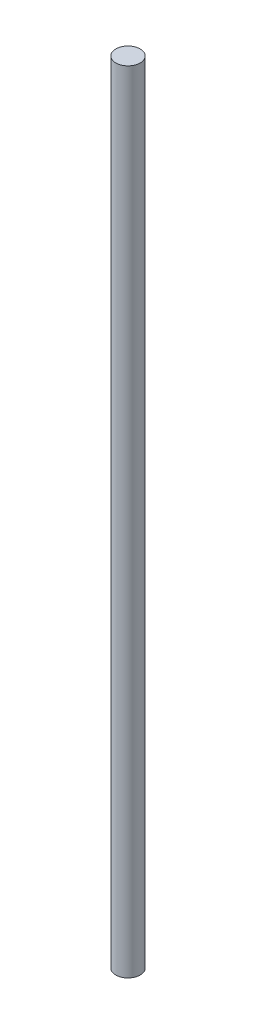
SolidWorks part; units mm, degrees
material "PVC 0.007 Plasticized"
ref_plane "Front Plane" through (0, 0, 0) normal (0, 0, 1) x (1, 0, 0)
ref_plane "Top Plane" through (0, 0, 0) normal (0, 1, 0) x (1, 0, 0)
ref_plane "Right Plane" through (0, 0, 0) normal (1, 0, 0) x (0, 0, -1)
sketch "Sketch1" plane through (0, 0, 0) normal (0, 1, 0) x (1, 0, 0)
  circle A1 centre (0, 0) radius 4.699
  dimension "D2" = 9.398
extrude "Boss-Extrude1" add sketch "Sketch1" along normal blind 304.8
